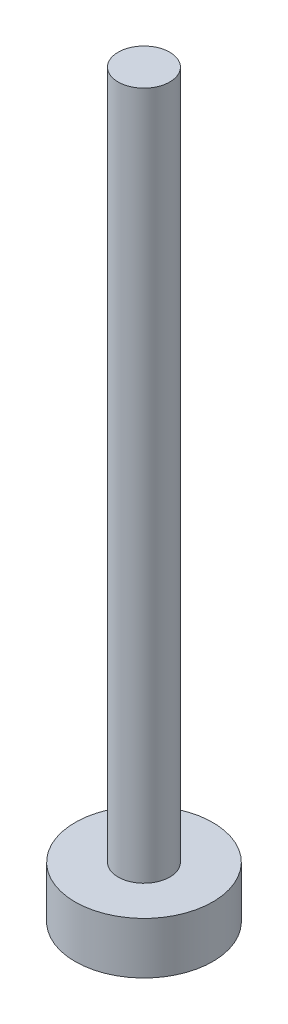
SolidWorks part; units mm, degrees
ref_plane "Front Plane" through (0, 0, 0) normal (0, 0, 1) x (1, 0, 0)
ref_plane "Top Plane" through (0, 0, 0) normal (0, 1, 0) x (1, 0, 0)
ref_plane "Right Plane" through (0, 0, 0) normal (1, 0, 0) x (0, 0, -1)
sketch "草圖1" plane through (0, 0, 0) normal (0, 1, 0) x (1, 0, 0)
  circle A0 centre (0, 0) radius 4
  dimension "D1" = 8
extrude "填料-伸長1" add sketch "草圖1" along normal blind 3
sketch "草圖2" plane through (0, 3, 0) normal (0, 1, 0) x (1, 0, 0)
  circle A0 centre (0, 0) radius 1.5
  dimension "D1" = 3
extrude "填料-伸長2" add sketch "草圖2" along normal blind 40
sketch "草圖3" plane through (0, 0, 0) normal (0, 0, 1) x (1, 0, 0)
  line L0 (0, -3.5412) -> (0, 7.9701)
  point P3 (0, -3.5412)
  dimension "D1" = 7.9701
  dimension "D2" = 3.5412
